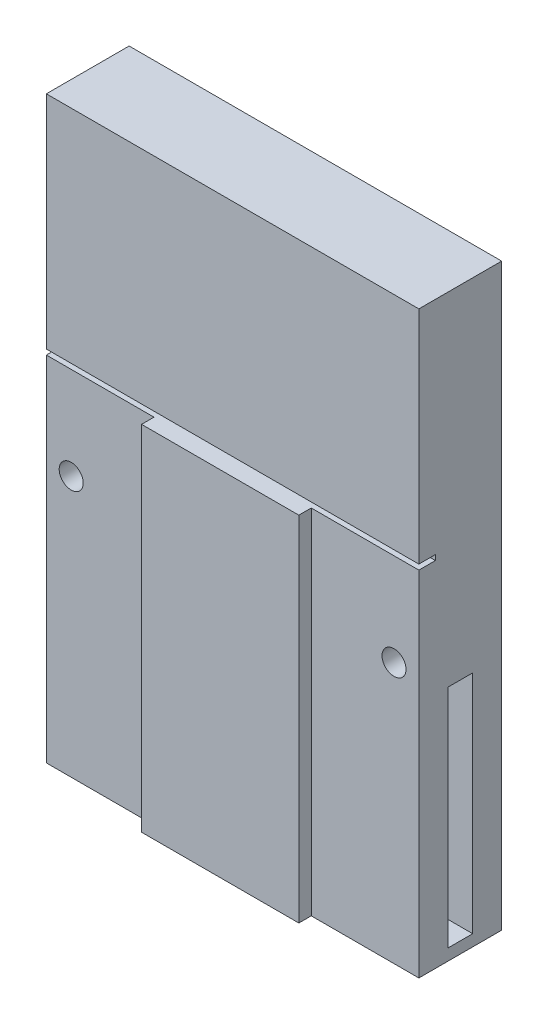
SolidWorks part; units mm, degrees
ref_plane "Front Plane" through (0, 0, 0) normal (0, 0, 1) x (1, 0, 0)
ref_plane "Top Plane" through (0, 0, 0) normal (0, 1, 0) x (1, 0, 0)
ref_plane "Right Plane" through (0, 0, 0) normal (1, 0, 0) x (0, 0, -1)
sketch "Sketch2" plane through (0, 0, 0) normal (0, 1, 0) x (1, 0, 0)
  line L1 (22.5, 5) -> (-22.5, 5)
  line L2 (22.5, 5) -> (22.5, -5)
  line L3 (22.5, -5) -> (-22.5, -5)
  line L4 (-22.5, 5) -> (-22.5, -5)
  line L5 (22.5, 5) -> (-22.5, -5) construction
  line L6 (22.5, -5) -> (-22.5, 5) construction
  point P0 (0, 0)
  dimension "D1" = 10
  dimension "D2" = 45
extrude "Boss-Extrude1" add sketch "Sketch2" along normal blind 40
sketch "Sketch3" plane through (0, 0, -5) normal (0, 0, -1) x (-1, 0, 0)
  line L0 (0, 0) -> (0, 40) construction
  line L1 (-22.5, 40) -> (22.5, 40) construction
  line L3 (22.5, 40) -> (22.5, 0) construction
  line L4 (-22.5, 40) -> (-22.5, 0) construction
  line L5 (-22.5, 0) -> (22.5, 0) construction
  line L6 (-22.5, 11.5) -> (22.5, 11.5) construction
  circle A0 centre (19.5, 2.25) radius 1.45
  circle A3 centre (-19.5, 2.25) radius 1.45
  circle A4 centre (-19.5, 20.75) radius 1.45
  circle A5 centre (19.5, 20.75) radius 1.45
  dimension "D3" = 2.9
  dimension "D4" = 3
  dimension "D1" = 3
  dimension "D2" = 2.25
sketch "Sketch4" plane through (0, 40, 0) normal (0, 1, 0) x (1, 0, 0)
  line L1 (-22.5, 5) -> (22.5, 5)
  line L2 (-22.5, 5) -> (-22.5, -5)
  line L3 (-22.5, -5) -> (22.5, -5)
  line L4 (22.5, 5) -> (22.5, -5)
extrude "Boss-Extrude2" add sketch "Sketch4" along normal blind 10
sketch "Sketch6" plane through (0, 0, -5) normal (0, 0, -1) x (-1, 0, 0)
  line L2 (-22.5, 23) -> (22.7712, 23) construction
  circle A1 centre (-19.5, 20.75) radius 1.45 construction
  dimension "D1" = 2.25
sketch "Sketch8" plane through (0, 0, 0) normal (0, -1, 0) x (1, 0, 0)
  line L1 (-22.5, 5) -> (22.5, 5)
  line L2 (-22.5, 5) -> (-22.5, -5)
  line L3 (-22.5, -5) -> (22.5, -5)
  line L4 (22.5, 5) -> (22.5, -5)
extrude "Boss-Extrude3" add sketch "Sketch8" along normal blind 20
sketch "Sketch9" plane through (0, 0, 5) normal (0, 0, 1) x (1, 0, 0)
  line L0 (22.5, 11.5) -> (-22.5, 11.5) construction
  line L1 (-22.5, 50) -> (-22.5, -20) construction
  line L2 (22.5, 50) -> (22.5, -20) construction
  circle A0 centre (19.5, 20.75) radius 1.45 construction
  circle A1 centre (19.5, 2.25) radius 1.45 construction
  circle A2 centre (19.5, 11.5) radius 1.45
  circle A3 centre (-19.5, 11.5) radius 1.45
  dimension "D1" = 18.5
  dimension "D2" = 3
  dimension "D3" = 3
  dimension "D4" = 3
extrude "Cut-Extrude2" cut sketch "Sketch9" against normal blind 20
sketch "Sketch10" plane through (0, 0, 5) normal (0, 0, 1) x (1, 0, 0)
  line L1 (-22.5, 50) -> (-22.5, -20) construction
  line L2 (-22.5, 23.2975) -> (22.5, 23.2975)
  line L3 (-22.5, 23.2975) -> (-22.5, 22.6713)
  line L4 (-22.5, 22.6713) -> (22.5, 22.6713)
  line L5 (22.5, 23.2975) -> (22.5, 22.6713)
  line L6 (22.5, 50) -> (22.5, -20) construction
extrude "Cut-Extrude3" cut sketch "Sketch10" against normal blind 2
sketch "Sketch11" plane through (0, 0, 5) normal (0, 0, 1) x (1, 0, 0)
  line L0 (-22.5, 22.6713) -> (22.5, 22.6713) construction
  line L1 (-9.5, 22.6713) -> (9.5, 22.6713)
  line L2 (-9.5, 22.6713) -> (-9.5, -20)
  line L3 (-9.5, -20) -> (9.5, -20)
  line L4 (9.5, 22.6713) -> (9.5, -20)
  line L5 (22.5, -20) -> (-22.5, -20) construction
  line L6 (22.5, 22.6713) -> (22.5, -20) construction
  line L8 (-22.5, 22.6713) -> (-22.5, -20) construction
  dimension "D1" = 19
  dimension "D2" = 13
  dimension "D3" = 13
extrude "Boss-Extrude4" add sketch "Sketch11" along normal blind 1.5
sketch "Sketch12" plane through (22.5, 0, 0) normal (1, 0, 0) x (0, 0, -1)
  line L0 (0, 8.6713) -> (0, -20) construction
  line L1 (5, -20) -> (-5, -20) construction
  line L2 (-3, 22.6713) -> (-5, 22.6713) construction
  line L3 (-1.5, 8.6713) -> (1.5, 8.6713)
  line L4 (-1.5, 8.6713) -> (-1.5, -18.615)
  line L5 (-1.5, -18.615) -> (1.5, -18.615)
  line L6 (1.5, 8.6713) -> (1.5, -18.615)
  dimension "D1" = 3
  dimension "D2" = 1.385
  dimension "D3" = 14
extrude "Cut-Extrude6" cut sketch "Sketch12" against normal blind 10
mirror "Mirror1" about plane through (0, 0, 0) normal (1, 0, 0) of "Cut-Extrude6"
